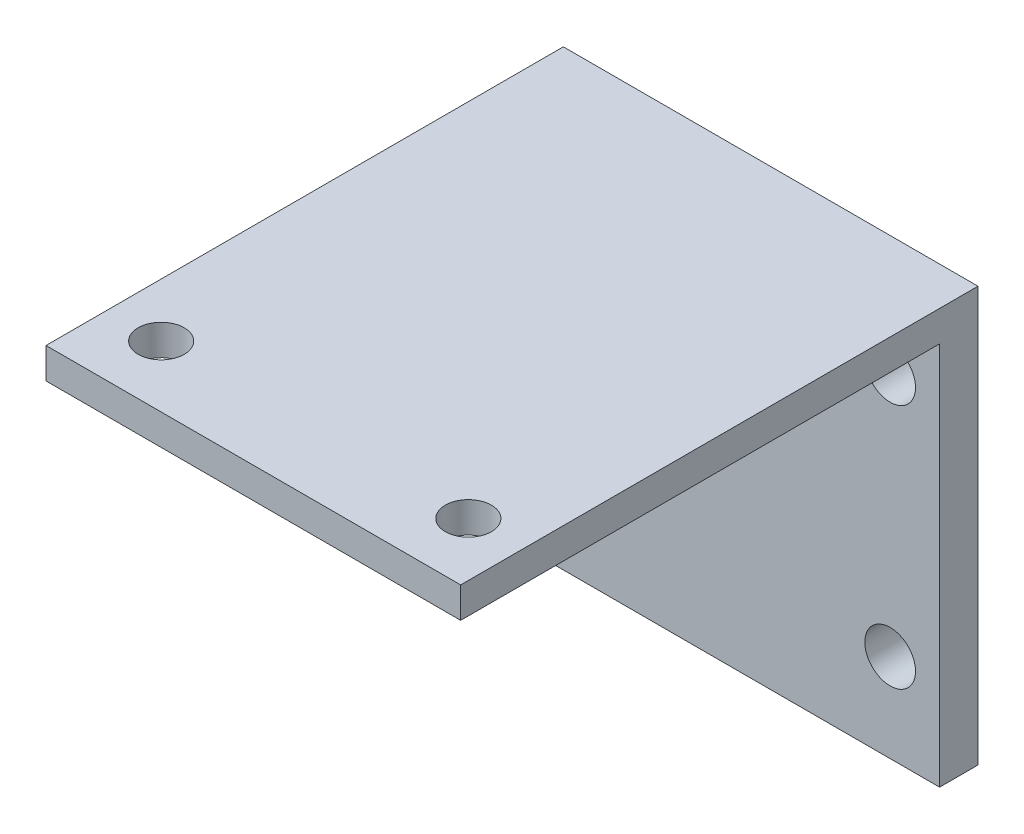
SolidWorks part; units mm, degrees
ref_plane "Plan de face" through (0, 0, 0) normal (0, 0, 1) x (1, 0, 0)
ref_plane "Plan de dessus" through (0, 0, 0) normal (0, 1, 0) x (1, 0, 0)
ref_plane "Plan de droite" through (0, 0, 0) normal (1, 0, 0) x (0, 0, -1)
sketch "Esquisse1" plane through (0, 0, 0) normal (0, 0, 1) x (1, 0, 0)
  line L1 (-27, -27) -> (27, -27)
  line L2 (-27, -27) -> (-27, 27)
  line L3 (-27, 27) -> (27, 27)
  line L4 (27, -27) -> (27, 27)
  line L5 (-27, -27) -> (27, 27) construction
  line L6 (-27, 27) -> (27, -27) construction
  line L7 (9, -27) -> (-9, -27)
  line L8 (9, -27) -> (9, 27)
  line L9 (9, 27) -> (-9, 27)
  line L10 (-9, -27) -> (-9, 27)
  line L11 (9, -27) -> (-9, 27) construction
  line L12 (9, 27) -> (-9, -27) construction
  circle A0 centre (9.88, 20) radius 3
  circle A1 centre (9.88, -20) radius 3
  point P0 (0, 0)
  point P7 (0, 0)
  dimension "D4" = 6
  dimension "D1" = 54
  dimension "D2" = 54
  dimension "D3" = 17.12
  dimension "D5" = 7
  dimension "D7" = 2
extrude "Boss.-Extru.1" add sketch "Esquisse1" along normal blind 67.37 contours L8 L1 L4 L3 | L1 L10 L3 L2 | L10 L1 L8 L3 A1 A0
sketch "Esquisse2" plane through (0, 0, 67.37) normal (0, 0, 1) x (1, 0, 0)
  line L8 (23, 23) -> (-23, 23)
  line L9 (-23, 23) -> (-23, -23)
  line L10 (-23, -23) -> (23, -23)
  line L11 (23, -23) -> (23, 23)
  line L12 (38.775, 23) -> (-47.1129, 23)
  line L13 (-47.1129, 23) -> (-47.1129, -35.7903)
  line L14 (-47.1129, -35.7903) -> (38.775, -35.7903)
  line L15 (38.775, -35.7903) -> (38.775, 23)
  dimension "D1" = 4
extrude "Enlèv. mat.-Extru.1" cut sketch "Esquisse2" against normal blind 62.37
sketch "Esquisse3" plane through (0, 23, 0) normal (0, -1, 0) x (1, 0, 0)
  line L0 (27, 67.37) -> (-27, 67.37) construction
  line L1 (-27, 67.37) -> (-27, 5) construction
  circle A0 centre (-20, 59.37) radius 3
  circle A1 centre (20, 59.37) radius 3
  dimension "D3" = 6
  dimension "D1" = 8
  dimension "D2" = 7
  dimension "D4" = 2
extrude "Enlèv. mat.-Extru.2" cut sketch "Esquisse3" against normal blind 62.37
hole_wizard "Dégagement M61" positions "Esquisse5" profile "Esquisse4" hole size "M6" standard "JIS" end condition through all
sketch "Esquisse5" plane through (0, 0, 0) normal (0, 0, -1) x (-1, 0, 0)
  point P0 (-20.5628, -15.5)
  point P2 (-20.5628, 16.5)
sketch "Esquisse4" plane through (20.5628, -15.5, 0) normal (1, 0, 0) x (0, 1, 0)
  line L0 (0, 0) -> (0, 67.37)
  line L1 (0, 67.37) -> (3.3, 67.37)
  line L2 (3.3, 67.37) -> (3.3, 0)
  line L5 (3.3, 0) -> (0, 0)
  line L11 (0, -6.35) -> (0, 107.95) construction
  dimension "Diamètre du perçage jusqu'au prochain" = 6.6
  dimension "Profondeur du perçage jusqu'au prochain" = 67.37
